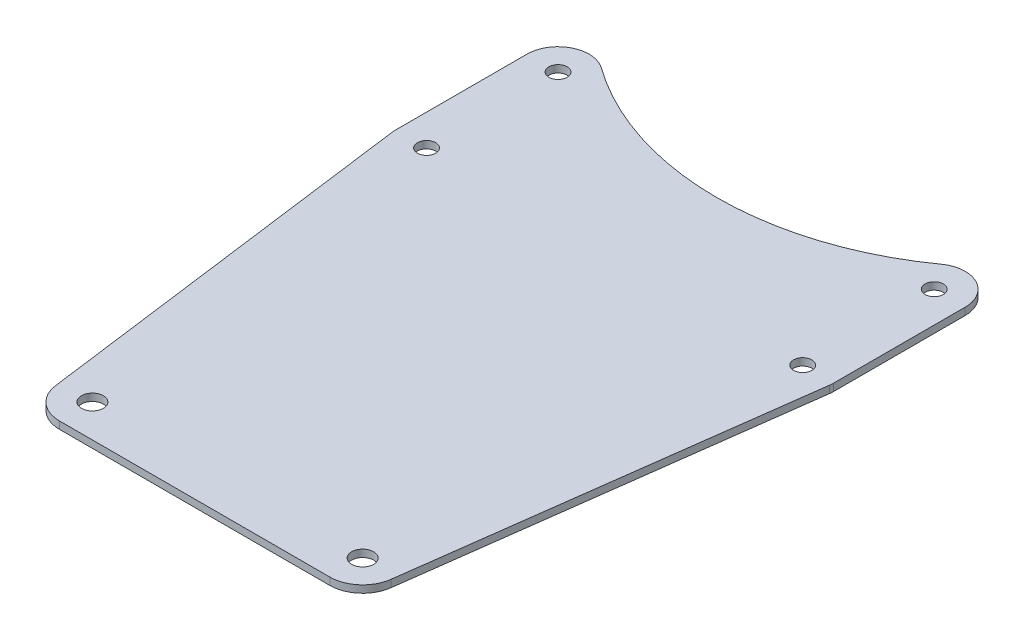
SolidWorks part; units mm, degrees
material "Skleněné vlákno-A"
ref_plane "Přední rovina" through (0, 0, 0) normal (0, 0, 1) x (1, 0, 0)
ref_plane "Horní rovina" through (0, 0, 0) normal (0, 1, 0) x (1, 0, 0)
ref_plane "Pravá rovina" through (0, 0, 0) normal (1, 0, 0) x (0, 0, -1)
sketch "Skica1" plane through (0, 0, 0) normal (0, 1, 0) x (1, 0, 0)
  line L0 (0, -46.9461) -> (0, 13.25) construction
  line L1 (-29.9634, -9.5563) -> (-22.9613, -62.589)
  line L2 (-18.5, -66.5) -> (18.5, -66.5)
  line L3 (-30, -9) -> (-30, 9)
  line L5 (30, -9) -> (30, 9)
  line L6 (29.9634, -9.5563) -> (22.9613, -62.589)
  circle A0 centre (-18.5, -62) radius 1.5 construction
  circle A1 centre (-25.75, 9) radius 1.25 construction
  circle A2 centre (-25.75, 9) radius 1.25
  arc A3 (-22.9613, -62.589) -> (-18.5, -66.5) centre (-18.5, -62) ccw
  arc A4 (-29.9634, -9.5563) -> (-30, -9) centre (-25.75, -9) cw
  arc A5 (-30, 9) -> (-23.2768, 12.4563) centre (-25.75, 9) cw
  arc A6 (30, 9) -> (23.2768, 12.4563) centre (25.75, 9) ccw
  arc A7 (29.9634, -9.5563) -> (30, -9) centre (25.75, -9) ccw
  arc A8 (22.9613, -62.589) -> (18.5, -66.5) centre (18.5, -62) cw
  circle A9 centre (25.75, 9) radius 1.25 construction
  circle A10 centre (25.75, 9) radius 1.25
  circle A11 centre (18.5, -62) radius 1.5 construction
  arc A12 (23.2768, 12.4563) -> (-23.2768, 12.4563) centre (0, 44.9861) cw
  circle A19 centre (-25.75, -9) radius 1.25 construction
  circle A20 centre (-25.75, -9) radius 1.25
  circle A21 centre (25.75, -9) radius 1.25 construction
  circle A22 centre (25.75, -9) radius 1.25
  circle A23 centre (-18.5, -62) radius 1.5
  circle A24 centre (18.5, -62) radius 1.5
  dimension "D1" = 3
  dimension "D3" = 40
  dimension "D2" = 3
extrude "Přidat vysunutím1" add sketch "Skica1" along normal mid plane 1
